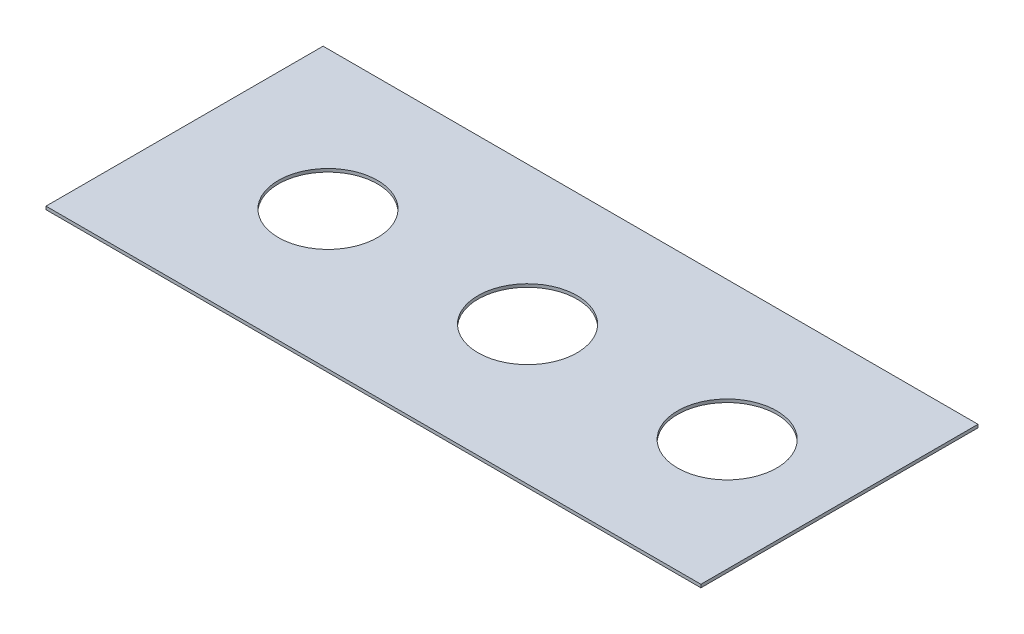
SolidWorks part; units mm, degrees
ref_plane "Front" through (0, 0, 0) normal (0, 0, 1) x (1, 0, 0)
ref_plane "Top" through (0, 0, 0) normal (0, 1, 0) x (1, 0, 0)
ref_plane "Right" through (0, 0, 0) normal (1, 0, 0) x (0, 0, -1)
sketch "Sketch1" plane through (0, 0, 0) normal (0, 1, 0) x (1, 0, 0)
  line L0 (-165.1, 0) -> (165.1, 0) construction
  line L1 (-165.1, -69.85) -> (165.1, -69.85)
  line L2 (-165.1, -69.85) -> (-165.1, 69.85)
  line L3 (-165.1, 69.85) -> (165.1, 69.85)
  line L4 (165.1, -69.85) -> (165.1, 69.85)
  line L5 (-165.1, -69.85) -> (165.1, 69.85) construction
  line L6 (-165.1, 69.85) -> (165.1, -69.85) construction
  circle A0 centre (-92.7862, 0) radius 24.9936
  circle A1 centre (7.8486, 0) radius 24.9936
  circle A2 centre (108.4834, 0) radius 24.9936
  point P0 (0, 0)
  dimension "D6" = 49.9872
  dimension "D1" = 330.2
  dimension "D2" = 139.7
  dimension "D3" = 72.3138
  dimension "D4" = 172.9486
  dimension "D5" = 273.5834
extrude "Boss-Extrude1" add sketch "Sketch1" along normal blind 1.5748
